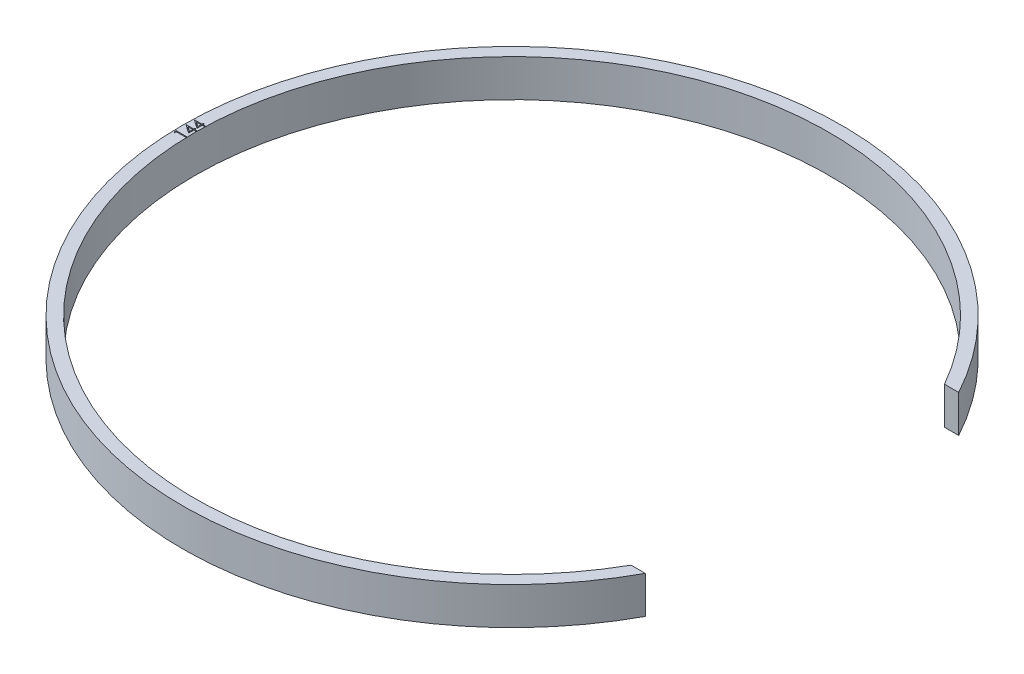
SolidWorks part; units mm, degrees
material "Acrylic (Medium-high impact)"
ref_plane "Front Plane" through (0, 0, 0) normal (0, 0, 1) x (1, 0, 0)
ref_plane "Top Plane" through (0, 0, 0) normal (0, 1, 0) x (1, 0, 0)
ref_plane "Right Plane" through (0, 0, 0) normal (1, 0, 0) x (0, 0, -1)
sketch "Sketch1" plane through (0, 0, 0) normal (0, 1, 0) x (1, 0, 0)
  circle A0 centre (0, 0) radius 51
  circle A1 centre (0, 0) radius 53
  dimension "D1" = 102
  dimension "D2" = 106
extrude "Boss-Extrude2" add sketch "Sketch1" along normal blind 6
sketch "Sketch2" plane through (0, 6, 0) normal (0, 1, 0) x (1, 0, 0)
  line L0 (0, 0) -> (0, 25.2)
  line L1 (0, 0) -> (0, -25.2)
  line L2 (0, 25.2) -> (76.8264, 25.2)
  line L3 (76.8264, 25.2) -> (76.8264, -25.2)
  line L4 (76.8264, -25.2) -> (0, -25.2)
extrude "Cut-Extrude1" cut sketch "Sketch2" against normal blind 10
sketch "Sketch3" plane through (0, 6, 0) normal (0, 1, 0) x (1, 0, 0)
  line L2 (-51, 14.4222) -> (-51, -14.4222) construction
  arc A1 (46.6257, 25.2) -> (46.6257, -25.2) centre (0, 0) ccw construction
  text T0 "144\r\n" font "Century Gothic" height 1.75
extrude "Cut-Extrude2" cut sketch "Sketch3" against normal blind 0.5
